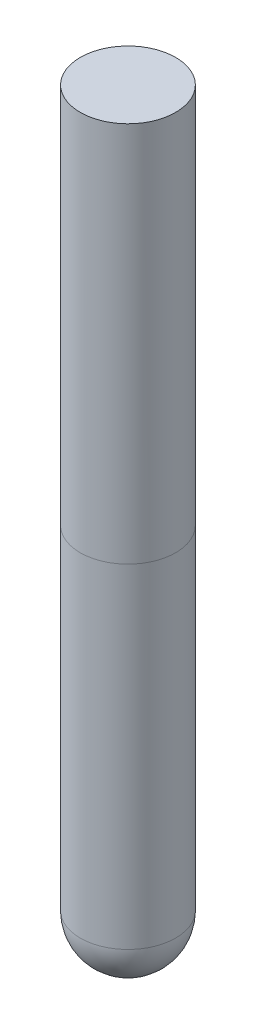
SolidWorks part; units mm, degrees
material "6061 Alloy"
ref_plane "Front Plane" through (0, 0, 0) normal (0, 0, 1) x (1, 0, 0)
ref_plane "Top Plane" through (0, 0, 0) normal (0, 1, 0) x (1, 0, 0)
ref_plane "Right Plane" through (0, 0, 0) normal (1, 0, 0) x (0, 0, -1)
sketch "Sketch1" plane through (0, 0, 0) normal (0, 0, 1) x (1, 0, 0)
  line L0 (0, 0) -> (3.175, 0)
  line L1 (3.175, 0) -> (3.175, -22.225)
  line L2 (0, 0) -> (0, -25.4)
  line L3 (4.2279, -25.4) -> (-2.7883, -25.4) construction
  arc A0 (3.175, -22.225) -> (0, -25.4) centre (0, -22.225) cw
  dimension "D1" = 3.175
  dimension "D3" = 25.4
revolve "Revolve1" add sketch "Sketch1" angle 360 about L2
sketch "Sketch3" plane through (0, 0, 0) normal (0, 1, 0) x (1, 0, 0)
  circle A0 centre (0, 0) radius 3.175
  dimension "D1" = 6.35
extrude "Boss-Extrude1" add sketch "Sketch3" along normal blind 25.4
split "Split1" trim tools "Top Plane" bodies to split 102 resulting bodies 103 104
ref_plane "Plane1" through (3.175, 0, 0) normal (1, 0, 0) x (0, 0, -1)
ref_plane "Plane2" through (0, 0, -3.175) normal (0, 0, -1) x (-1, 0, 0)
ref_plane "Plane3" through (0, -25.4, 0) normal (0, -1, 0) x (-1, 0, 0)
